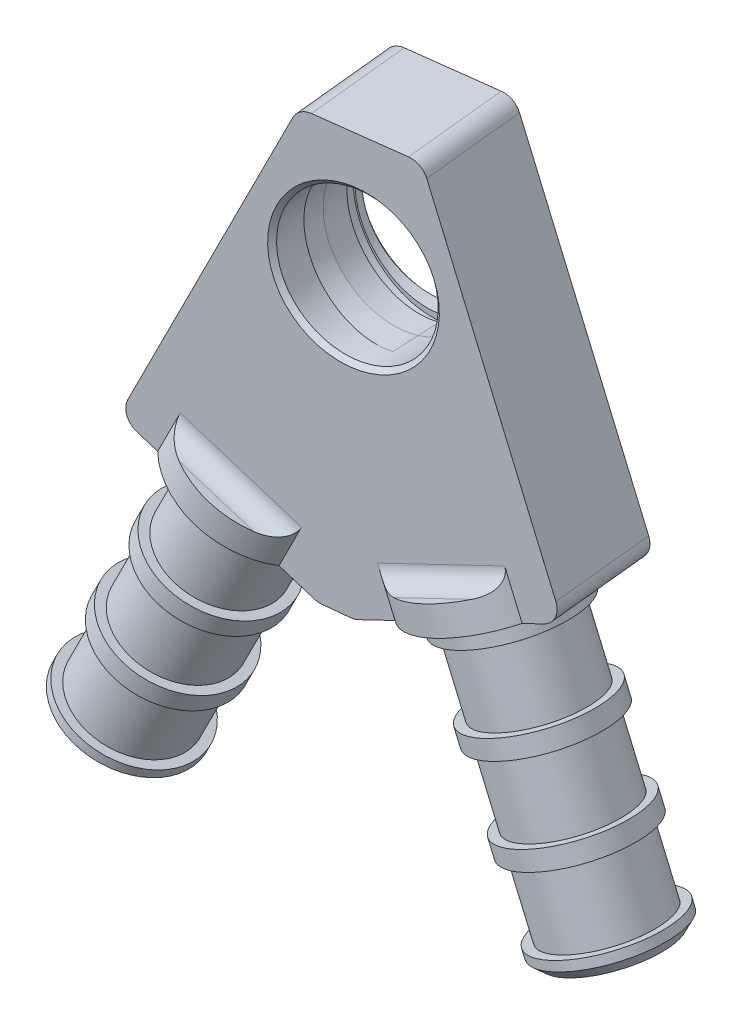
SolidWorks part; units mm, degrees
ref_plane "Front Plane" through (0, 0, 0) normal (0, 0, 1) x (1, 0, 0)
ref_plane "Top Plane" through (0, 0, 0) normal (0, 1, 0) x (1, 0, 0)
ref_plane "Right Plane" through (0, 0, 0) normal (1, 0, 0) x (0, 0, -1)
sketch3d "3DSketch1"
  line L0 (1150, 574, 138) -> (1280, 250, 132)
  line L1 (1280, 250, 132) -> (1020, 290, 165)
  line L2 (1020, 290, 165) -> (1150, 574, 138)
  point P0 (1020, 290, 165)
  point P1 (1280, 250, 132)
  point P2 (1150, 574, 138)
  point P3 (1150, 574, 138)
ref_plane "Plane1" through (40.2285, 10.5074, 304.2154) normal (0.131, 0.0342, 0.9908) x (0.9914, -0.0045, -0.1309)
sketch "Sketch1" plane through (40.2285, 10.5074, 304.2154) normal (0.131, 0.0342, 0.9908) x (0.9914, -0.0045, -0.1309)
  line L0 (1113.5581, 582.4609) -> (1125.7924, 582.4609)
  line L1 (1125.7924, 582.4609) -> (1140.8827, 545.2215)
  line L2 (1140.8827, 545.2215) -> (1120.4931, 536.9592)
  line L4 (1116.8644, 537.0437) -> (1096.8813, 546.2457)
  line L5 (1096.8813, 546.2457) -> (1113.5581, 582.4609)
  line L6 (988.2907, 284.1316) -> (1119.4211, 568.8943) construction
  line L7 (1119.4211, 568.8943) -> (1250.5514, 245.2945) construction
  line L8 (1106.8729, 541.6447) -> (1119.4211, 568.8943)
  line L9 (1119.4211, 568.8943) -> (1130.6879, 541.0904)
  line L10 (1116.8644, 537.0437) -> (1120.4931, 536.9592)
  circle A0 centre (1119.4211, 568.8943) radius 8
  point P15 (1130.6879, 541.0904)
  point P16 (1106.8729, 541.6447)
  dimension "D1" = 22
  dimension "D4" = 16
  dimension "D2" = 22
  dimension "D3" = 30
extrude "Boss-Extrude1" add sketch "Sketch1" along normal mid plane 12 contours A0 L9 L2 L1 L0 L5 L4 L8 | A0 L8 L4 L10 L2 L9
fillet "Fillet1" radius 2 6 edges at (1171.2766, 550.2443, 136.007) (1151.0628, 542.0791, 138.962) (1147.4654, 542.1799, 139.4342) (1127.6546, 551.4668, 141.7332) (1156.3164, 587.5297, 136.6974) (1144.1876, 587.5851, 138.2994)
ref_plane "Plane2" through (395.9916, 865.0893, -82.2444) normal (-0.4147, -0.9059, 0.0861) x (-0.91, 0.4128, -0.0392)
sketch "Sketch2" plane through (395.9916, 865.0893, -82.2444) normal (-0.4147, -0.9059, 0.0861) x (-0.91, 0.4128, -0.0392)
  circle A0 centre (-814.9344, -191.706) radius 9
extrude "Boss-Extrude2" add sketch "Sketch2" against normal blind 3
sketch "Sketch4" plane through (395.9916, 865.0893, -82.2444) normal (-0.4147, -0.9059, 0.0861) x (-0.91, 0.4128, -0.0392)
  circle A0 centre (-814.9344, -191.706) radius 6
  dimension "D1" = 12
extrude "Boss-Extrude4" add sketch "Sketch4" along normal blind 31
sketch "Sketch7" plane through (395.9916, 865.0893, -82.2444) normal (-0.4147, -0.9059, 0.0861) x (-0.91, 0.4128, -0.0392)
  circle A0 centre (-814.9344, -191.706) radius 7
  circle A1 centre (-814.9344, -191.706) radius 6
  dimension "D1" = 14
  dimension "D2" = 12
extrude "Boss-Extrude5" add sketch "Sketch7" along normal blind 2
pattern_linear "LPattern1" count 4 spacing 9.6667 along (-0.4147, -0.9059, 0.0861) of "Boss-Extrude5"
chamfer "Chamfer1" distance 1 angle 45 1 edges at (1131.0702, 515.8273, 143.2535)
ref_plane "Plane5" through (383.1369, 837.0068, -79.5746) normal (-0.4147, -0.9059, 0.0861) x (-0.91, 0.4128, -0.0392)
sketch "Sketch8" plane through (383.1369, 837.0068, -79.5746) normal (-0.4147, -0.9059, 0.0861) x (-0.91, 0.4128, -0.0392)
  circle A0 centre (-814.9344, -191.706) radius 4.5
ref_plane "Plane6" through (701.3399, -328.7734, -81.3873) normal (-0.9005, 0.4221, 0.1045) x (0.0946, -0.0444, 0.9945)
sketch "Sketch9" plane through (701.3399, -328.7734, -81.3873) normal (-0.9005, 0.4221, 0.1045) x (0.0946, -0.0444, 0.9945)
  line L0 (225.8775, 947.0805) -> (230.3606, 947.4702)
  line L1 (221.3944, 946.6908) -> (230.3606, 947.4702) construction
  line L2 (230.3606, 947.4702) -> (228.5132, 968.7234)
  line L3 (230.0075, 968.8533) -> (218.0526, 967.8141) construction
  line L4 (220.5951, 1007.8513) -> (241.2991, 769.6651) construction
  line L6 (223.6404, 972.8168) -> (225.8775, 947.0805)
  arc A0 (228.5132, 968.7234) -> (223.6404, 972.8168) centre (224.0301, 968.3337) ccw
  dimension "D1" = 4.5
revolve "Cut-Revolve1" cut sketch "Sketch9" angle 360 about L6
ref_plane "Plane8" through (-28.6092, 71.3028, 1.3204) normal (0.3723, -0.9279, -0.0172) x (-0.9281, -0.3723, -0.0069)
sketch "Sketch10" plane through (-28.6092, 71.3028, 1.3204) normal (0.3723, -0.9279, -0.0172) x (-0.9281, -0.3723, -0.0069)
  circle A0 centre (-1281.9468, -127.3485) radius 9
  dimension "D1" = 18
extrude "Boss-Extrude6" add sketch "Sketch10" against normal blind 3
sketch "Sketch11" plane through (-28.6092, 71.3028, 1.3204) normal (0.3723, -0.9279, -0.0172) x (-0.9281, -0.3723, -0.0069)
  circle A0 centre (-1281.9468, -127.3485) radius 6
  dimension "D1" = 12
extrude "Boss-Extrude7" add sketch "Sketch11" along normal blind 31
sketch "Sketch12" plane through (-28.6092, 71.3028, 1.3204) normal (0.3723, -0.9279, -0.0172) x (-0.9281, -0.3723, -0.0069)
  circle A0 centre (-1281.9468, -127.3485) radius 6
  circle A1 centre (-1281.9468, -127.3485) radius 7
  dimension "D1" = 12
  dimension "D2" = 14
extrude "Boss-Extrude8" add sketch "Sketch12" along normal blind 2
pattern_linear "LPattern2" count 4 spacing 9.6667 along (0.3723, -0.9279, -0.0172) of "Boss-Extrude8"
chamfer "Chamfer2" distance 1 angle 45 1 edges at (1179.2083, 520.0021, 136.9518)
ref_plane "Plane9" through (1149.5504, 464.3514, -168.0514) normal (0.9188, 0.3711, -0.1343) x (0.3723, -0.9279, -0.0172)
sketch "Sketch13" plane through (1149.5504, 464.3514, -168.0514) normal (0.9188, 0.3711, -0.1343) x (0.3723, -0.9279, -0.0172)
  line L0 (-45.8396, -307.0436) -> (-45.8396, -302.5436)
  line L1 (-45.8396, -313.0436) -> (-45.8396, -301.0436) construction
  line L2 (-45.8396, -302.5436) -> (-67.1729, -302.5436)
  line L3 (-67.1729, -301.0436) -> (-67.1729, -313.0436) construction
  line L4 (-106.8396, -307.0436) -> (242.3194, -307.0436) construction
  line L5 (-71.6729, -307.0436) -> (-45.8396, -307.0436)
  arc A0 (-67.1729, -302.5436) -> (-71.6729, -307.0436) centre (-67.1729, -307.0436) ccw
  dimension "D1" = 4.5
revolve "Cut-Revolve2" cut sketch "Sketch13" angle 360 about L5
fillet "Fillet2" radius 2 4 edges at (1159.2666, 548.7402, 131.5913) (1138.0179, 549.3357, 134.3806) (1160.8388, 549.1508, 143.4808) (1139.5901, 549.7463, 146.2701)
chamfer "Chamfer3" distance 0.5 angle 45 2 edges at (1158.7171, 574.2053, 142.896) (1157.1448, 573.7947, 131.0065)
ref_plane "Plane10" through (0, 0, 138) normal (0, 0, 1) x (1, 0, 0)
sketch "Sketch14" plane through (0, 0, 138) normal (0, 0, 1) x (1, 0, 0)
  circle A0 centre (1150, 574) radius 8
  dimension "D1" = 16
extrude "Cut-Extrude1" cut sketch "Sketch14" along normal blind 3 and the other way blind 2
sketch "Sketch15" plane through (0, 0, 138) normal (0, 0, 1) x (1, 0, 0)
  circle A0 centre (1150, 574) radius 8.75
  dimension "D1" = 17.5
extrude "Cut-Extrude2" cut sketch "Sketch15" against normal blind 1.05 from offset 2.5 offset against normal yes
